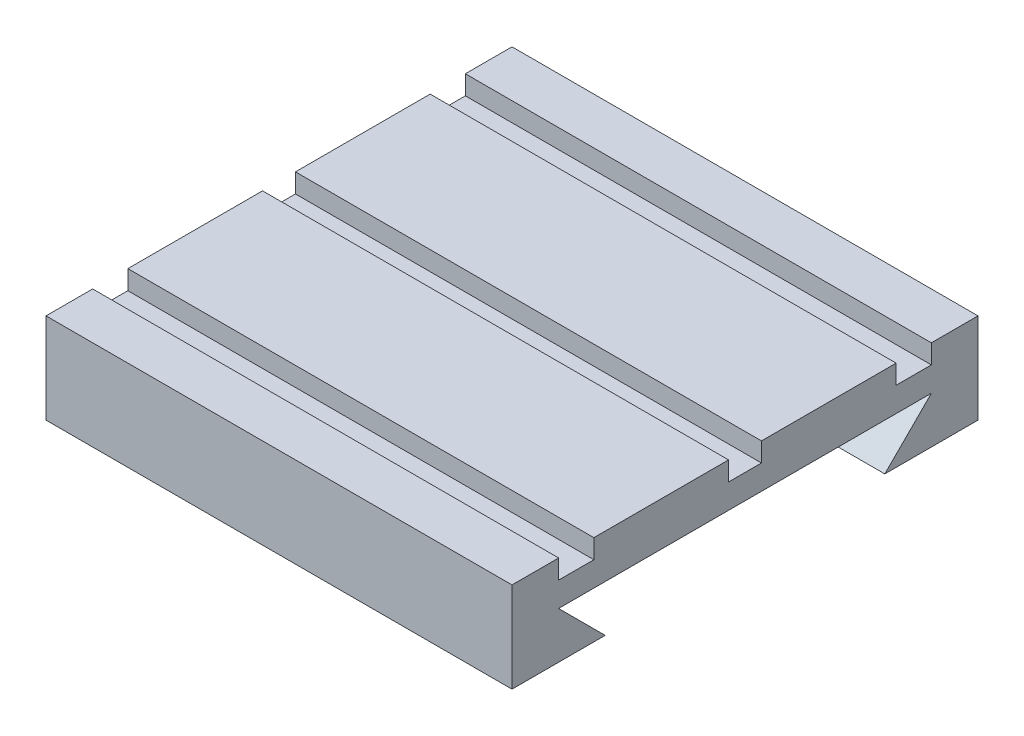
SolidWorks part; units mm, degrees
material "Aleación 1060"
ref_plane "Alzado" through (0, 0, 0) normal (0, 0, 1) x (1, 0, 0)
ref_plane "Planta" through (0, 0, 0) normal (0, 1, 0) x (1, 0, 0)
ref_plane "Vista lateral" through (0, 0, 0) normal (1, 0, 0) x (0, 0, -1)
sketch "Croquis1" plane through (0, 0, 0) normal (1, 0, 0) x (0, 0, -1)
  line L0 (-30, 3.5) -> (-40, 13.5)
  line L1 (50, -3.5) -> (-50, -3.5) construction
  line L2 (50, -3.5) -> (50, 3.5) construction
  line L3 (50, 3.5) -> (-50, 3.5) construction
  line L4 (-50, -3.5) -> (-50, 3.5) construction
  line L5 (50, -3.5) -> (-50, 3.5) construction
  line L6 (50, 3.5) -> (-50, -3.5) construction
  line L7 (-40, 13.5) -> (40, 13.5)
  line L8 (40, 13.5) -> (30, 3.5)
  line L9 (30, 3.5) -> (-30, 3.5) construction
  line L10 (-30, 3.5) -> (-50, 3.5)
  line L11 (-50, 3.5) -> (-50, 18.7709)
  line L12 (-50, 18.7709) -> (50, 18.7709)
  line L13 (50, 18.7709) -> (50, 3.5)
  line L14 (50, 3.5) -> (30, 3.5)
  point P0 (0, 0)
  dimension "D1" = 100
  dimension "D2" = 7
  dimension "D3" = 45
  dimension "D4" = 20
  dimension "D5" = 20
  dimension "D6" = 10
extrude "Saliente-Extruir1" add sketch "Croquis1" along normal blind 100
sketch "Croquis2" plane through (100, 0, 0) normal (1, 0, 0) x (0, 0, -1)
  line L0 (50, 18.7709) -> (-50, 18.7709) construction
  line L1 (-50, 18.7709) -> (-39.9891, 18.7709)
  line L2 (-50, 18.7709) -> (-50, 22.8777)
  line L3 (-50, 22.8777) -> (-39.9891, 22.8777)
  line L4 (-39.9891, 18.7709) -> (-39.9891, 22.8777)
  line L5 (-32.4347, 18.7709) -> (-3.5309, 18.7709)
  line L6 (-32.4347, 18.7709) -> (-32.4347, 22.8777)
  line L7 (-32.4347, 22.8777) -> (-3.5309, 22.8777)
  line L8 (-3.5309, 18.7709) -> (-3.5309, 22.8777)
  line L9 (0, 0) -> (0, 31.4174) construction
  line L10 (3.5309, 18.7709) -> (3.5309, 22.8777)
  line L11 (32.4347, 22.8777) -> (3.5309, 22.8777)
  line L12 (32.4347, 18.7709) -> (32.4347, 22.8777)
  line L13 (32.4347, 18.7709) -> (3.5309, 18.7709)
  line L14 (39.9891, 18.7709) -> (39.9891, 22.8777)
  line L15 (50, 22.8777) -> (39.9891, 22.8777)
  line L16 (50, 18.7709) -> (50, 22.8777)
  line L17 (50, 18.7709) -> (39.9891, 18.7709)
extrude "Saliente-Extruir2" add sketch "Croquis2" against normal blind 100
